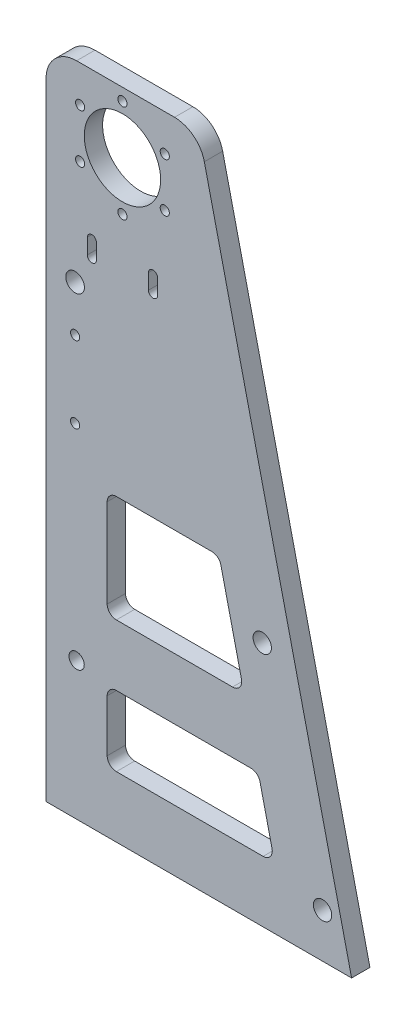
SolidWorks part; units mm, degrees
material "Policarbonato"
ref_plane "Plano frontal" through (0, 0, 0) normal (0, 0, 1) x (1, 0, 0)
ref_plane "Plano superior" through (0, 0, 0) normal (0, 1, 0) x (1, 0, 0)
ref_plane "Plano direito" through (0, 0, 0) normal (1, 0, 0) x (0, 0, -1)
sketch "Esboço1" plane through (0, 0, 0) normal (0, 0, 1) x (1, 0, 0)
  line L0 (0, 0) -> (0, 215)
  line L2 (100, 0) -> (0, 0)
  line L3 (0, 215) -> (50, 215)
  line L4 (50, 215) -> (100, 0)
  line L5 (10, 75.4302) -> (10, 15) construction
  line L6 (25, 215) -> (25, 175) construction
  line L7 (10, 15) -> (85.7122, 15) construction
  line L8 (85.7122, 15) -> (71.6586, 75.4302) construction
  line L9 (71.6586, 75.4302) -> (10, 75.4302) construction
  line L10 (20, 95) -> (20, 66)
  line L11 (23, 63) -> (61.0374, 63)
  line L12 (63.9594, 66.6795) -> (57.2152, 95.6795)
  line L13 (54.2932, 98) -> (23, 98)
  line L14 (20, 40) -> (20, 23)
  line L15 (23, 20) -> (71.0374, 20)
  line L16 (73.9594, 23.6795) -> (70.0059, 40.6795)
  line L17 (23, 43) -> (67.0839, 43)
  circle A0 centre (25, 195) radius 12.5
  circle A1 centre (25, 195) radius 16 construction
  circle A2 centre (25, 211) radius 1.5
  arc A8 (70.0059, 40.6795) -> (67.0839, 43) centre (67.0839, 40) ccw
  arc A9 (71.0374, 20) -> (73.9594, 23.6795) centre (71.0374, 23) ccw
  arc A10 (20, 23) -> (23, 20) centre (23, 23) ccw
  arc A11 (20, 40) -> (23, 43) centre (23, 40) cw
  arc A12 (57.2152, 95.6795) -> (54.2932, 98) centre (54.2932, 95) ccw
  arc A13 (61.0374, 63) -> (63.9594, 66.6795) centre (61.0374, 66) ccw
  arc A14 (20, 66) -> (23, 63) centre (23, 66) ccw
  arc A15 (20, 95) -> (23, 98) centre (23, 95) cw
  circle A16 centre (38.8564, 203) radius 1.5
  circle A17 centre (38.8564, 187) radius 1.5
  circle A18 centre (25, 179) radius 1.5
  circle A19 centre (11.1436, 187) radius 1.5
  circle A20 centre (11.1436, 203) radius 1.5
  circle A21 centre (10, 45) radius 2.5
  point P26 (22.5, 105)
  point P49 (20, 63)
  point P55 (25, 175)
  point P56 (25, 195)
  dimension "D3" = 20
  dimension "D4" = 25
  dimension "D6" = 32
  dimension "D7" = 3
  dimension "D21" = 3
  dimension "D15" = 10
  dimension "D16" = 45
  dimension "D17" = 5
  dimension "D1" = 215
  dimension "D2" = 100
  dimension "D5" = 50
  dimension "D9" = 25
  dimension "D10" = 6
  dimension "D11" = 20
  dimension "D12" = 20
  dimension "D13" = 15
  dimension "D14" = 20
  dimension "D18" = 10
  dimension "D20" = 20
  dimension "D22" = 23
  dimension "D8" = 35
extrude "Ressalto-extrusão2" add sketch "Esboço1" along normal blind 6
fillet "Filete1" radius 10 2 edges at (0, 215, 3) (50, 215, 3)
sketch "Esboço2" plane through (0, 0, 6) normal (0, 0, 1) x (1, 0, 0)
  line L0 (0, 0) -> (100, 0) construction
  line L1 (0, 205) -> (0, 0) construction
  line L2 (15, 164.21) -> (35, 164.21) construction
  line L3 (15, 161.71) -> (15, 166.71) construction
  line L4 (13.5, 161.71) -> (13.5, 166.71)
  line L5 (16.5, 161.71) -> (16.5, 166.71)
  line L6 (35, 161.71) -> (35, 166.71) construction
  line L7 (33.5, 161.71) -> (33.5, 166.71)
  line L8 (36.5, 161.71) -> (36.5, 166.71)
  circle A0 centre (9.5, 137) radius 1.5
  circle A1 centre (90.5, 14.5) radius 3
  circle A2 centre (9.5, 112) radius 1.5
  circle A3 centre (9.5, 152) radius 3.05
  circle A4 centre (15, 164.21) radius 1.5 construction
  circle A5 centre (35, 164.21) radius 1.5 construction
  arc A6 (13.5, 161.71) -> (16.5, 161.71) centre (15, 161.71) ccw
  arc A7 (16.5, 166.71) -> (13.5, 166.71) centre (15, 166.71) ccw
  arc A8 (33.5, 161.71) -> (36.5, 161.71) centre (35, 161.71) ccw
  arc A9 (36.5, 166.71) -> (33.5, 166.71) centre (35, 166.71) ccw
  point P2 (9.5, 112)
  point P3 (9.5, 137)
  point P18 (25, 195)
  point P20 (25, 164.21)
  point P22 (15, 164.21)
  point P30 (35, 164.21)
  dimension "D4" = 3
  dimension "D7" = 6
  dimension "D8" = 6.1
  dimension "D10" = 3
  dimension "D1" = 112
  dimension "D2" = 25
  dimension "D3" = 9.5
  dimension "D5" = 14.5
  dimension "D6" = 9.5
  dimension "D9" = 15
  dimension "D11" = 20
  dimension "D12" = 30.79
  dimension "D13" = 5
extrude "Corte-extrusão1" cut sketch "Esboço2" against normal through all
sketch "Esboço3" plane through (0, 0, 6) normal (0, 0, 1) x (1, 0, 0)
  circle A1 centre (70.7598, 80.3986) radius 3
extrude "Corte-extrusão2" cut sketch "Esboço3" against normal through all
